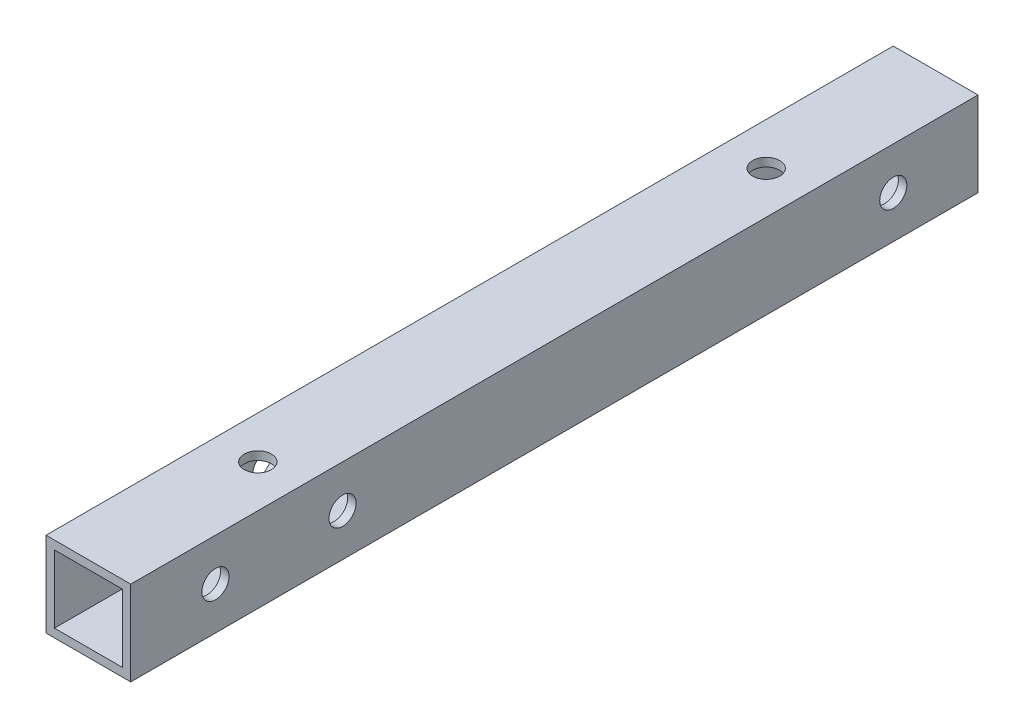
SolidWorks part; units mm, degrees
ref_plane "正面" through (0, 0, 0) normal (0, 0, 1) x (1, 0, 0)
ref_plane "平面" through (0, 0, 0) normal (0, 1, 0) x (1, 0, 0)
ref_plane "右側面" through (0, 0, 0) normal (1, 0, 0) x (0, 0, -1)
sketch "ｽｹｯﾁ1" plane through (0, 0, 0) normal (0, 0, 1) x (1, 0, 0)
  line L0 (-4, 4) -> (-4, -4)
  line L1 (-5, 5) -> (5, 5)
  line L2 (-5, 5) -> (-5, -5)
  line L3 (-5, -5) -> (5, -5)
  line L4 (5, 5) -> (5, -5)
  line L5 (-5, 5) -> (5, -5) construction
  line L6 (-5, -5) -> (5, 5) construction
  line L7 (-4, -4) -> (4, -4)
  line L8 (4, 4) -> (4, -4)
  line L9 (-4, 4) -> (4, 4)
  point P0 (0, 0)
  dimension "D1" = 10
  dimension "D2" = 10
  dimension "D3" = 1
extrude "ﾎﾞｽ - 押し出し1" add sketch "ｽｹｯﾁ1" along normal blind 100
sketch "ｽｹｯﾁ2" plane through (0, 5, 0) normal (0, 1, 0) x (1, 0, 0)
  line L0 (0, -5.5) -> (0, 5.5) construction
  line L1 (5, -100) -> (-5, -100) construction
  circle A0 centre (0, -20) radius 1.6
  circle A1 centre (0, -80) radius 1.6
  dimension "D1" = 3.2
  dimension "D2" = 3.2
  dimension "D3" = 60
  dimension "D4" = 20
extrude "ｶｯﾄ - 押し出し1" cut sketch "ｽｹｯﾁ2" against normal through all
sketch "ｽｹｯﾁ3" plane through (-5, 0, 0) normal (-1, 0, 0) x (0, 0, 1)
  line L0 (5.5, 0) -> (-5.5, 0) construction
  line L1 (0, -5.5) -> (0, 5.5) construction
  circle A0 centre (10, 0) radius 1.6
  circle A1 centre (90, 0) radius 1.6
  dimension "D1" = 3.2
  dimension "D2" = 10
  dimension "D3" = 3.2
  dimension "D4" = 80
extrude "ｶｯﾄ - 押し出し2" cut sketch "ｽｹｯﾁ3" against normal through all
sketch "ｽｹｯﾁ4" plane through (5, 0, 0) normal (1, 0, 0) x (0, 0, -1)
  circle A0 centre (-75, 0) radius 1.6
  circle A1 centre (-90, 0) radius 1.6 construction
  dimension "D1" = 3.2
  dimension "D2" = 15
extrude "ｶｯﾄ - 押し出し3" cut sketch "ｽｹｯﾁ4" against normal through all
